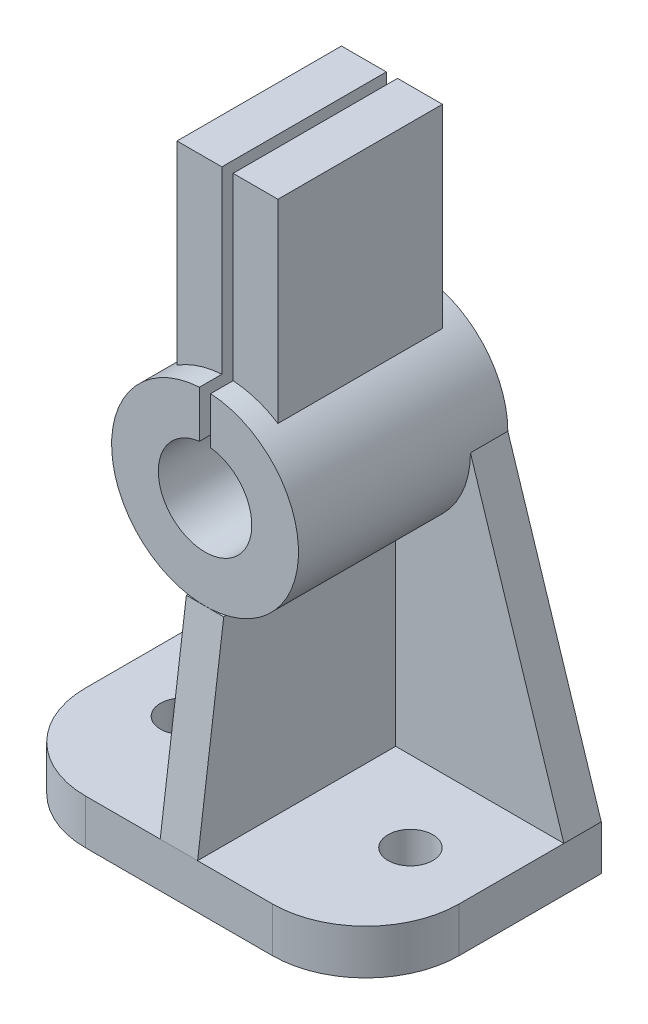
SolidWorks part; units mm, degrees
ref_plane "Front Plane" through (0, 0, 0) normal (0, 0, 1) x (1, 0, 0)
ref_plane "Top Plane" through (0, 0, 0) normal (0, 1, 0) x (1, 0, 0)
ref_plane "Right Plane" through (0, 0, 0) normal (1, 0, 0) x (0, 0, -1)
sketch "Sketch2" plane through (0, 0, 0) normal (0, 1, 0) x (1, 0, 0)
  line L1 (-25, -31.5) -> (25, -31.5)
  line L2 (-50, -6.5) -> (-50, 31.5)
  line L3 (-50, 31.5) -> (50, 31.5)
  line L4 (50, -6.5) -> (50, 31.5)
  line L5 (-50, -31.5) -> (50, 31.5) construction
  line L6 (-50, 31.5) -> (50, -31.5) construction
  arc A0 (25, -31.5) -> (50, -6.5) centre (25, -6.5) ccw
  arc A1 (-25, -31.5) -> (-50, -6.5) centre (-25, -6.5) cw
  point P0 (0, 0)
  dimension "D3" = 25
  dimension "D1" = 63
  dimension "D2" = 100
extrude "Boss-Extrude1" add sketch "Sketch2" along normal blind 12
ref_plane "Plane1" through (0, 0, -31.5) normal (0, 0, -1) x (-1, 0, 0)
sketch "Sketch3" plane through (0, 0, -31.5) normal (0, 0, -1) x (-1, 0, 0)
  line L0 (-50, 0) -> (50, 0) construction
  circle A0 centre (0, 90) radius 25
  circle A1 centre (0, 90) radius 12.5
  dimension "D1" = 50
  dimension "D3" = 25
  dimension "D2" = 90
extrude "Boss-Extrude2" add sketch "Sketch3" against normal blind 56 separate body
sketch "Sketch5" plane through (0, 0, -31.5) normal (0, 0, -1) x (-1, 0, 0)
  line L0 (-25, 90) -> (-50, 12)
  line L1 (-50, 12) -> (50, 12)
  line L2 (50, 12) -> (25, 90)
  circle A0 centre (0, 90) radius 25 construction
  arc A1 (25, 90) -> (-25, 90) centre (0, 90) ccw
extrude "Boss-Extrude5" add sketch "Sketch5" against normal blind 10
sketch "Sketch7" plane through (0, 0, 0) normal (0, -1, 0) x (-1, 0, 0)
  line L0 (0, 29.9215) -> (0, -22.7028) construction
  circle A0 centre (-30.443, 0) radius 6
  circle A1 centre (30.443, 0) radius 6
  dimension "D1" = 12
extrude "Cut-Extrude1" cut sketch "Sketch7" against normal up to next
ref_plane "Plane2" through (0, 0, 0) normal (-1, 0, 0) x (0, 0, 1)
sketch "Sketch8" plane through (0, 0, 0) normal (-1, 0, 0) x (0, 0, 1)
  line L0 (24.5, 65) -> (31.5, 12)
  line L1 (31.5, 12) -> (-21.5, 12)
  line L2 (-21.5, 12) -> (-21.5, 65)
  line L3 (-21.5, 12) -> (-21.5, 90) construction
  line L4 (-21.5, 65) -> (-21.5, 90) construction
  line L5 (-21.5, 65) -> (24.5, 65)
extrude "Boss-Extrude8" add sketch "Sketch8" along normal mid plane 10 separate body
ref_plane "Plane3" through (0, 115, 0) normal (0, 1, 0) x (1, 0, 0)
sketch "Sketch10" plane through (0, 115, 0) normal (0, 1, 0) x (1, 0, 0)
  line L0 (25, 31.5) -> (-25, 31.5) construction
  line L1 (-13.5, 25.5) -> (13.5, 25.5)
  line L2 (-13.5, 25.5) -> (-13.5, -18.5)
  line L3 (-13.5, -18.5) -> (13.5, -18.5)
  line L4 (13.5, 25.5) -> (13.5, -18.5)
  line L7 (-25, 21.5) -> (-25, 31.5) construction
  dimension "D1" = 27
  dimension "D2" = 44
  dimension "D3" = 6
  dimension "D4" = 11.5
extrude "Boss-Extrude9" add sketch "Sketch10" along normal blind 48 separate body
sketch "Sketch11" plane through (0, 115, 0) normal (0, -1, 0) x (1, 0, 0)
  line L4 (-13.5, 18.5) -> (-13.5, -25.5)
  line L5 (-13.5, -25.5) -> (13.5, -25.5)
  line L6 (13.5, -25.5) -> (13.5, 18.5)
  line L7 (13.5, 18.5) -> (-13.5, 18.5)
  line L8 (-13.5, 18.5) -> (-13.5, -25.5)
  line L9 (-13.5, -25.5) -> (13.5, -25.5)
  line L10 (13.5, -25.5) -> (13.5, 18.5)
  line L11 (13.5, 18.5) -> (-13.5, 18.5)
  dimension "D1" = 0
extrude "Boss-Extrude10" add sketch "Sketch11" along normal up to next
sketch "Sketch14" plane through (0, 115, 0) normal (0, 1, 0) x (1, 0, 0)
  line L0 (25, 31.5) -> (-25, 31.5) construction
  line L1 (-1.5, 31.5) -> (1.5, 31.5)
  line L2 (-1.5, 31.5) -> (-1.5, -26.744)
  line L3 (-1.5, -26.744) -> (1.5, -26.744)
  line L4 (1.5, 31.5) -> (1.5, -26.744)
  point P6 (0, 31.5)
  point P7 (0, 31.5)
  dimension "D1" = 3
  dimension "D2" = 0
extrude "Cut-Extrude4" cut sketch "Sketch14" against normal up to surface and the other way through all up to face at (-12.5, 90, 24.5)
